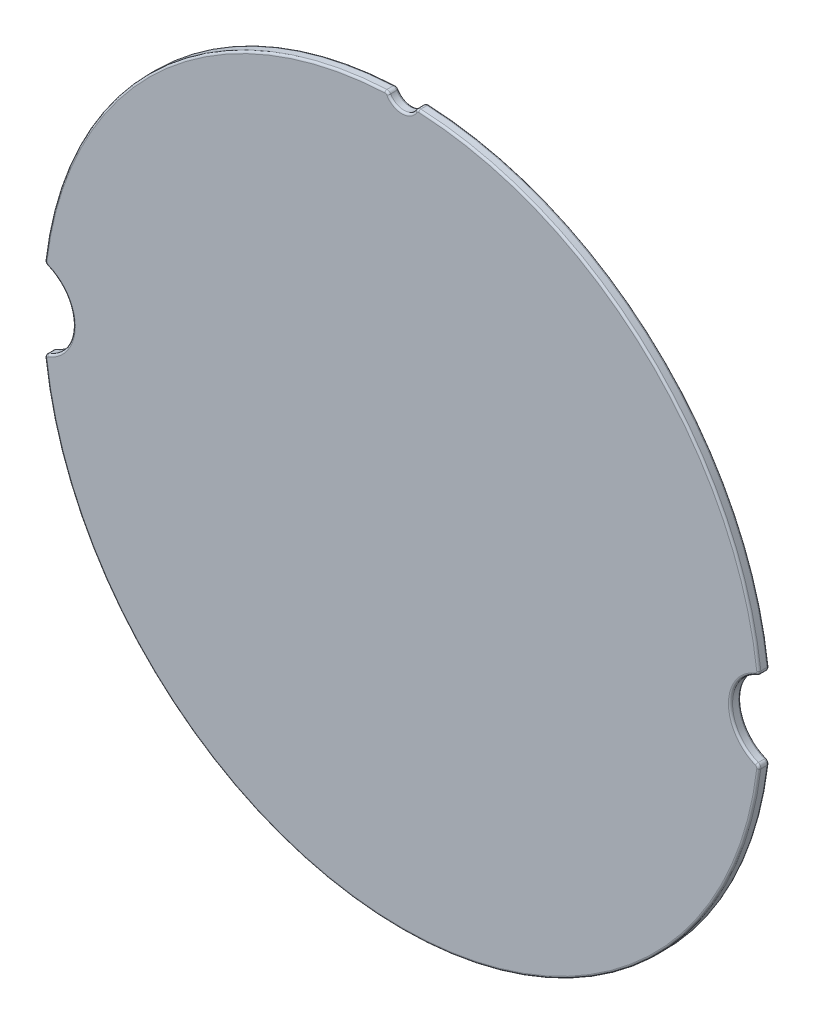
SolidWorks part; units mm, degrees
material "AISI 1010 Steel, hot rolled bar"
ref_plane "Front" through (0, 0, 0) normal (0, 0, 1) x (1, 0, 0)
ref_plane "Top" through (0, 0, 0) normal (0, 1, 0) x (1, 0, 0)
ref_plane "Right" through (0, 0, 0) normal (1, 0, 0) x (0, 0, -1)
ref_plane "Plane1" through (0, 0, -13) normal (0, 0, 1) x (1, 0, 0)
sketch "Sketch1" plane through (0, 0, -13) normal (0, 0, 1) x (1, 0, 0)
  line L0 (18, 0) -> (-18, 0) construction
  line L1 (0, 0) -> (0, 17.7651) construction
  arc A0 (0.8267, 17.4805) -> (0.6452, 17.3827) centre (0.8172, 17.2807) ccw
  arc A1 (0.6452, 17.3827) -> (-0.6452, 17.3827) centre (0, 17.7651) cw
  arc A2 (-0.6452, 17.3827) -> (-0.8267, 17.4805) centre (-0.8172, 17.2807) ccw
  arc A3 (-0.8267, 17.4805) -> (-17.3778, 2.0647) centre (0, 0) ccw
  arc A4 (-17.3778, 2.0647) -> (-17.2538, 1.8556) centre (-17.1792, 2.0411) ccw
  arc A5 (-17.2538, 1.8556) -> (-17.2538, -1.8556) centre (-18, 0) cw
  arc A6 (-17.2538, -1.8556) -> (-17.3778, -2.0647) centre (-17.1792, -2.0411) ccw
  arc A7 (-17.3778, -2.0647) -> (17.3778, -2.0647) centre (0, 0) ccw
  arc A8 (17.3778, -2.0647) -> (17.2538, -1.8556) centre (17.1792, -2.0411) ccw
  arc A9 (17.2538, -1.8556) -> (17.2538, 1.8556) centre (18, 0) cw
  arc A10 (17.2538, 1.8556) -> (17.3778, 2.0647) centre (17.1792, 2.0411) ccw
  arc A11 (17.3778, 2.0647) -> (0.8267, 17.4805) centre (0, 0) ccw
  dimension "D1" = 17.5
  dimension "D2" = 2
  dimension "D4" = 0.75
  dimension "D5" = 0.2
  dimension "D3" = 36
  dimension "D6" = 17.7651
extrude "Boss-Extrude1" add sketch "Sketch1" against normal blind 0.5
fillet "Fillet1" radius 0.1 12 edges at (0, -17.5, -13.5) (17.3512, -1.9392, -13.5) (-17.3512, -1.9392, -13.5) (16, 0, -13.5) (-16, 0, -13.5) (17.3512, 1.9392, -13.5) (-17.3512, 1.9392, -13.5) (11.9273, 12.8058, -13.5) (-11.9273, 12.8058, -13.5) (0.7223, 17.4568, -13.5) (-0.7223, 17.4568, -13.5) (0, 17.0151, -13.5)
fillet "Fillet2" radius 0.1 12 edges at (-17.3512, -1.9392, -13) (0, -17.5, -13) (-16, 0, -13) (17.3512, -1.9392, -13) (-17.3512, 1.9392, -13) (16, 0, -13) (-11.9273, 12.8058, -13) (17.3512, 1.9392, -13) (-0.7223, 17.4568, -13) (11.9273, 12.8058, -13) (0, 17.0151, -13) (0.7223, 17.4568, -13)
